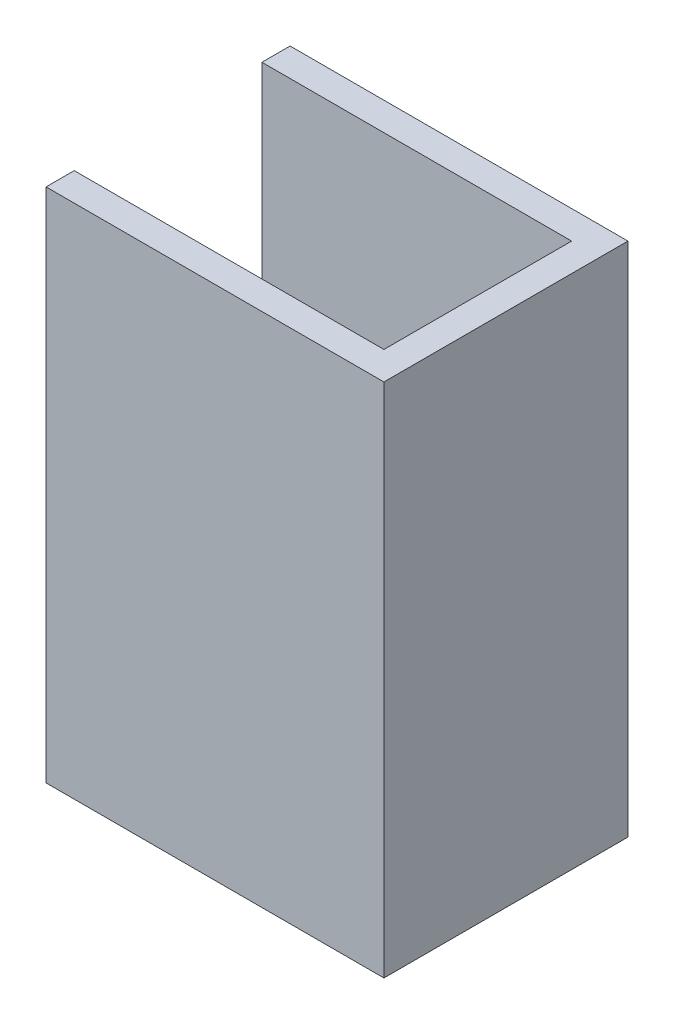
SolidWorks part; units mm, degrees
ref_plane "Plan de face" through (0, 0, 0) normal (0, 0, 1) x (1, 0, 0)
ref_plane "Plan de dessus" through (0, 0, 0) normal (0, 1, 0) x (1, 0, 0)
ref_plane "Plan de droite" through (0, 0, 0) normal (1, 0, 0) x (0, 0, -1)
sketch "Esquisse1" plane through (0, 0, 0) normal (0, 0, 1) x (1, 0, 0)
  line L1 (-45.1545, 40.7324) -> (-9.1545, 40.7324)
  line L2 (-45.1545, 40.7324) -> (-45.1545, -39.2676)
  line L3 (-45.1545, -39.2676) -> (-9.1545, -39.2676)
  line L4 (-9.1545, 40.7324) -> (-9.1545, -39.2676)
  dimension "D1" = 36
  dimension "D2" = 80
extrude "Boss.-Extru.1" add sketch "Esquisse1" along normal blind 3
sketch "Esquisse2" plane through (0, 0, 0) normal (0, 0, -1) x (-1, 0, 0)
  line L1 (9.1545, 40.7324) -> (12.1545, 40.7324)
  line L2 (9.1545, 40.7324) -> (9.1545, -14.2676)
  line L3 (9.1545, -14.2676) -> (12.1545, -14.2676)
  line L4 (12.1545, 40.7324) -> (12.1545, -14.2676)
  dimension "D1" = 55
  dimension "D2" = 3
extrude "Boss.-Extru.2" add sketch "Esquisse2" along normal blind 23
sketch "Esquisse3" plane through (-12.1545, 0, 0) normal (-1, 0, 0) x (0, 0, 1)
  line L0 (-23, -14.2676) -> (0, -14.2676) construction
  line L1 (-23, 40.7324) -> (-20, 40.7324)
  line L2 (-23, 40.7324) -> (-23, -14.2676)
  line L3 (-23, -14.2676) -> (-20, -14.2676)
  line L4 (-20, 40.7324) -> (-20, -14.2676)
  dimension "D1" = 3
extrude "Boss.-Extru.3" add sketch "Esquisse3" along normal blind 33
sketch "Esquisse4" plane through (0, 0, 0) normal (0, 0, -1) x (-1, 0, 0)
  line L0 (45.1545, 40.7324) -> (45.1545, -39.2676) construction
  line L1 (9.1545, -39.2676) -> (45.1545, -39.2676)
  line L2 (9.1545, -39.2676) -> (9.1545, -14.2676)
  line L3 (9.1545, -14.2676) -> (45.1545, -14.2676)
  line L4 (45.1545, -39.2676) -> (45.1545, -14.2676)
extrude "Enlèv. mat.-Extru.1" cut sketch "Esquisse4" against normal blind 33
